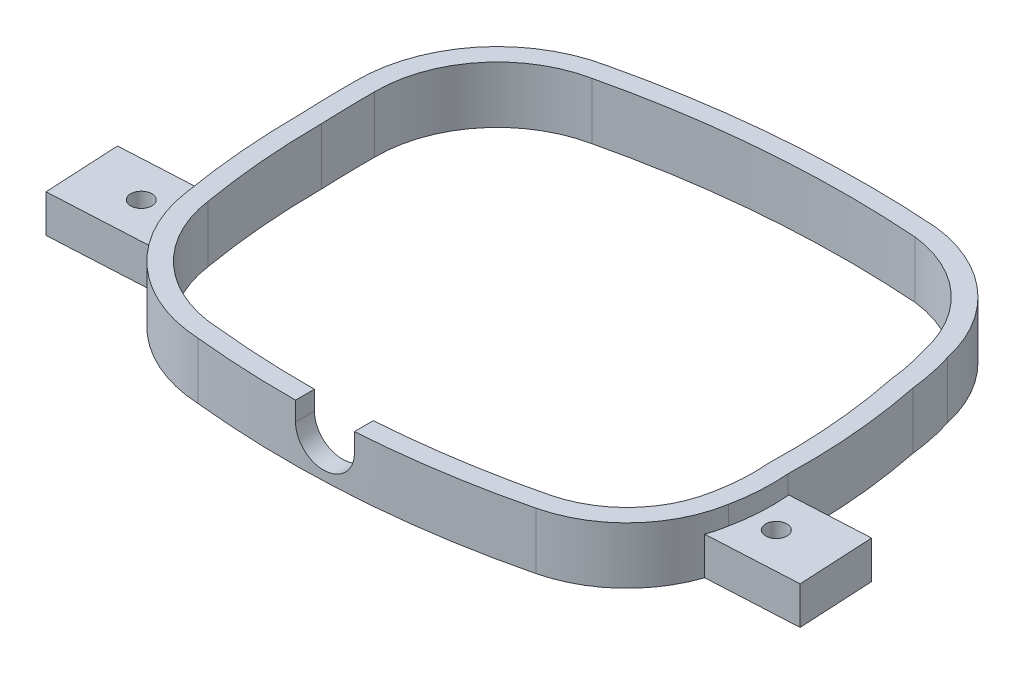
SolidWorks part; units mm, degrees
ref_plane "Front Plane" through (0, 0, 0) normal (0, 0, 1) x (1, 0, 0)
ref_plane "Top Plane" through (0, 0, 0) normal (0, 1, 0) x (1, 0, 0)
ref_plane "Right Plane" through (0, 0, 0) normal (1, 0, 0) x (0, 0, -1)
sketch "Sketch1" plane through (0, 0, 0) normal (0, 1, 0) x (1, 0, 0)
  line L0 (-300.4519, 73.9266) -> (-365.632, 18.4418) construction
  dimension "D1" = 85.598
sketch "Sketch2" plane through (0, 0, 0) normal (0, 1, 0) x (1, 0, 0)
  arc A0 (-25.8695, 31.9234) -> (-39.2064, 15.3989) centre (-22.5858, 15.6287) ccw construction
  arc A1 (-37.3082, -13.9314) -> (-21.4291, -28.3402) centre (-20.7653, -11.6546) ccw construction
  arc A2 (39.9218, -13.6412) -> (29.5483, -24.8653) centre (26.2462, -11.4078) cw construction
  arc A3 (23.2281, 35.9054) -> (37.0676, 23.1161) centre (21.2657, 19.8993) cw construction
  arc A4 (40.368, -5.6877) -> (38.467, 16.437) centre (-54.1087, -2.6614) ccw construction
  arc A5 (29.5483, -24.8653) -> (-21.4291, -28.3402) centre (-5.9093, 119.642) cw construction
  arc A6 (-39.0275, 6.3841) -> (-37.3082, -13.9314) centre (81.858, 6.3841) ccw construction
  arc A7 (-25.8695, 31.9234) -> (23.2281, 35.9054) centre (11.7644, -127.4219) cw construction
  arc A8 (-39.2064, 15.3989) -> (-39.0275, 6.3841) centre (146.711, 14.58) ccw construction
  arc A9 (40.368, -5.6877) -> (39.9218, -13.6412) centre (13.9173, -8.1928) cw construction
  arc A10 (37.0676, 23.1161) -> (38.467, 16.437) centre (6.853, 13.2993) cw construction
  arc A11 (-26.5502, 35.025) -> (-42.3815, 15.3851) centre (-22.5858, 15.6287) ccw construction
  arc A12 (-42.3815, 15.3851) -> (-42.2025, 6.314) centre (146.711, 14.58) ccw construction
  arc A13 (-42.2025, 6.314) -> (-40.4463, -14.4167) centre (81.858, 6.3841) ccw construction
  arc A14 (-40.4463, -14.4167) -> (-21.662, -31.5082) centre (-20.7653, -11.6546) ccw construction
  arc A15 (30.3049, -27.9488) -> (-21.662, -31.5082) centre (-5.9093, 119.642) cw construction
  arc A16 (43.0434, -14.2246) -> (30.3049, -27.9488) centre (26.2462, -11.4078) cw construction
  arc A17 (43.5475, -5.5925) -> (43.0434, -14.2246) centre (13.9173, -8.1928) cw construction
  arc A18 (43.5475, -5.5925) -> (41.6094, 16.9184) centre (-54.1087, -2.6614) ccw construction
  arc A19 (40.1413, 23.9294) -> (41.6094, 16.9184) centre (6.853, 13.2993) cw construction
  arc A20 (23.5293, 39.0671) -> (40.1413, 23.9294) centre (21.2657, 19.8993) cw construction
  arc A21 (-26.5502, 35.025) -> (23.5293, 39.0671) centre (11.7644, -127.4219) cw construction
  arc A22 (-26.6867, 35.6452) -> (-43.0165, 15.3826) centre (-22.5858, 15.6287) ccw
  arc A23 (-43.0165, 15.3826) -> (-42.8375, 6.2999) centre (146.711, 14.58) ccw
  arc A24 (-42.8375, 6.2999) -> (-41.0738, -14.5141) centre (81.858, 6.3841) ccw
  arc A25 (-41.0738, -14.5141) -> (-21.7094, -32.1417) centre (-20.7653, -11.6546) ccw
  arc A26 (30.4562, -28.5655) -> (-21.7094, -32.1417) centre (-5.9093, 119.642) cw
  arc A27 (43.6676, -14.3415) -> (30.4562, -28.5655) centre (26.2462, -11.4078) cw
  arc A28 (44.1833, -5.5743) -> (43.6676, -14.3415) centre (13.9173, -8.1928) cw
  arc A29 (44.1833, -5.5743) -> (42.2378, 17.0152) centre (-54.1087, -2.6614) ccw
  arc A30 (40.7557, 24.0928) -> (42.2378, 17.0152) centre (6.853, 13.2993) cw
  arc A31 (23.5889, 39.6994) -> (40.7557, 24.0928) centre (21.2657, 19.8993) cw
  arc A32 (-26.6867, 35.6452) -> (23.5889, 39.6994) centre (11.7644, -127.4219) cw
  arc A33 (-27.3713, 38.7458) -> (-46.1916, 15.371) centre (-22.5858, 15.6287) ccw
  arc A34 (-46.1916, 15.371) -> (-46.0124, 6.2293) centre (146.711, 14.58) ccw
  arc A35 (-46.0124, 6.2293) -> (-44.2113, -15.0029) centre (81.858, 6.3841) ccw
  arc A36 (-44.2113, -15.0029) -> (-21.9498, -35.3088) centre (-20.7653, -11.6546) ccw
  arc A37 (31.2128, -31.6491) -> (-21.9498, -35.3088) centre (-5.9093, 119.642) cw
  arc A38 (46.7886, -14.9276) -> (31.2128, -31.6491) centre (26.2462, -11.4078) cw
  arc A39 (47.3621, -5.4874) -> (46.7886, -14.9276) centre (13.9173, -8.1928) cw
  arc A40 (47.3621, -5.4874) -> (45.3788, 17.5018) centre (-54.1087, -2.6614) ccw
  arc A41 (43.8264, 24.9124) -> (45.3788, 17.5018) centre (6.853, 13.2993) cw
  arc A42 (23.8837, 42.8615) -> (43.8264, 24.9124) centre (21.2657, 19.8993) cw
  arc A43 (-27.3713, 38.7458) -> (23.8837, 42.8615) centre (11.7644, -127.4219) cw
  dimension "D1" = 3.175
  dimension "D2" = 3.81
extrude "Boss-Extrude1" add sketch "Sketch2" along normal blind 9.525
sketch "Sketch3" plane through (0, 0, 0) normal (0, 1, 0) x (1, 0, 0)
  line L0 (-59.2512, -23.6033) -> (125.5708, -23.6033) construction
  line L1 (-59.2512, -23.6033) -> (61.2335, -17.289)
  line L2 (-59.2512, -23.6033) -> (-59.9159, -10.9207)
  line L3 (-59.9159, -10.9207) -> (60.5688, -4.6064)
  line L4 (61.2335, -17.289) -> (60.5688, -4.6064)
  line L5 (60.9011, -10.9477) -> (-59.5835, -17.262) construction
  circle A0 centre (51.3892, -11.4462) radius 1.778
  circle A1 centre (-50.0716, -16.7635) radius 1.778
  arc A2 (30.4562, -28.5655) -> (43.6676, -14.3415) centre (26.2462, -11.4078) ccw construction
  arc A3 (42.526, -18.2694) -> (43.6676, -14.3415) centre (26.2462, -11.4078) ccw
  arc A4 (43.6676, -14.3415) -> (44.1833, -5.5743) centre (13.9173, -8.1928) ccw construction
  arc A5 (43.6676, -14.3415) -> (44.1737, -5.4656) centre (13.9173, -8.1928) ccw
  arc A6 (-41.0738, -14.5141) -> (-21.7094, -32.1417) centre (-20.7653, -11.6546) ccw construction
  arc A7 (-42.8375, 6.2999) -> (-41.0738, -14.5141) centre (81.858, 6.3841) ccw construction
  arc A8 (-41.0738, -14.5141) -> (-38.1727, -22.4986) centre (-20.7653, -11.6546) ccw
  arc A9 (-41.7605, -9.9692) -> (-41.0738, -14.5141) centre (81.858, 6.3841) ccw
  arc A10 (42.526, -18.2694) -> (44.1737, -5.4656) centre (9.6157, -7.5262) ccw
  arc A11 (-38.1727, -22.4986) -> (-41.7605, -9.9692) centre (-9.5452, -7.5228) cw
  dimension "D4" = 3.556
  dimension "D6" = 9.525
  dimension "D1" = 3
  dimension "D2" = 12.7
  dimension "D3" = 120.65
  dimension "D5" = 101.6
extrude "Boss-Extrude2" add sketch "Sketch3" along normal blind 6.35 contours A5 A3 L1 L4 L3 A0 | A8 A11 L3 L2 L1 A1 | A0
sketch "Sketch4" plane through (0, 0, 0) normal (0, 0, 1) x (1, 0, 0)
  line L0 (0, 11.1125) -> (0, 9.525) construction
  line L1 (-4.7625, 9.525) -> (4.7625, 9.525)
  line L2 (-4.7625, 9.525) -> (-4.7625, 6.35)
  line L3 (-21.9498, 0) -> (31.2128, 0) construction
  line L4 (4.7625, 9.525) -> (4.7625, 6.35)
  line L5 (31.2128, 9.525) -> (-21.9498, 9.525) construction
  arc A0 (-4.7625, 6.35) -> (4.7625, 6.35) centre (0, 6.35) ccw
  dimension "D2" = 4.7625
  dimension "D3" = 6.35
  dimension "D1" = 9.525
extrude "Cut-Extrude1" cut sketch "Sketch4" along normal blind 62.992
